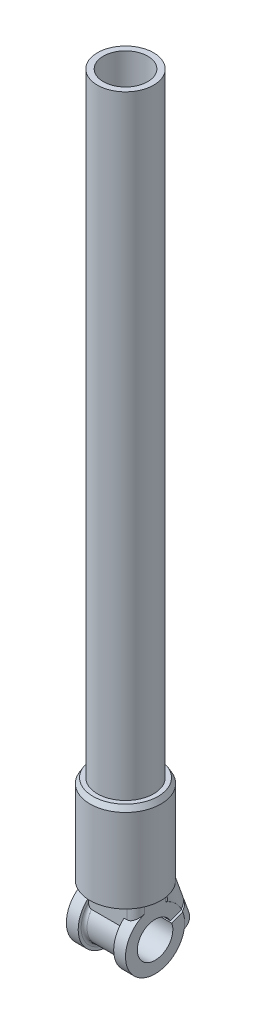
SolidWorks part; units mm, degrees
material "6061 Alloy"
ref_plane "Front Plane" through (0, 0, 0) normal (0, 0, 1) x (1, 0, 0)
ref_plane "Top Plane" through (0, 0, 0) normal (0, 1, 0) x (1, 0, 0)
ref_plane "Right Plane" through (0, 0, 0) normal (1, 0, 0) x (0, 0, -1)
sketch "Sketch1" plane through (0, 0, 0) normal (0, 0, 1) x (1, 0, 0)
  line L0 (20, -12) -> (-20, -12)
  line L1 (-20, -12) -> (-20, -20)
  line L2 (-20, -20) -> (-12, -20)
  line L3 (-12, -20) -> (-12, -18)
  line L4 (-10, -16) -> (10, -16)
  line L5 (12, -18) -> (12, -20)
  line L6 (12, -20) -> (20, -20)
  line L7 (20, -20) -> (20, -12)
  line L8 (-0.7979, 0) -> (-13.3837, 0) construction
  arc A0 (10, -16) -> (12, -18) centre (10, -18) cw
  arc A1 (-12, -18) -> (-10, -16) centre (-10, -18) cw
  point P8 (0, -16)
  point P10 (0, -12)
  point P13 (12, -16)
  point P16 (-12, -16)
  dimension "D6" = 2
  dimension "D1" = 40
  dimension "D2" = 12
  dimension "D3" = 8
  dimension "D4" = 4
  dimension "D5" = 24
revolve "Revolve1" add sketch "Sketch1" angle 360 about L8
sketch "Sketch3" plane through (0, 0, 0) normal (0, 1, 0) x (1, 0, 0)
  line L1 (-14, -13) -> (14, -13)
  line L2 (-20, -7) -> (-20, 7)
  line L3 (-14, 13) -> (14, 13)
  line L4 (20, -7) -> (20, 7)
  line L5 (-20, -13) -> (20, 13) construction
  line L6 (-20, 13) -> (20, -13) construction
  arc A0 (14, -13) -> (20, -7) centre (14, -7) ccw
  arc A1 (14, 13) -> (20, 7) centre (14, 7) cw
  arc A2 (-14, -13) -> (-20, -7) centre (-14, -7) cw
  arc A3 (-20, 7) -> (-14, 13) centre (-14, 7) cw
  point P0 (0, 0)
  dimension "D3" = 6
  dimension "D1" = 40
  dimension "D2" = 26
extrude "Boss-Extrude3" add sketch "Sketch3" against normal up to surface (15.6726 mm away) from offset 25
sketch "Sketch7" plane through (0, 0, 0) normal (0, 0, 1) x (1, 0, 0)
  line L0 (0, 25) -> (-19, 25)
  line L1 (-14, 25) -> (14, 25) construction
  line L2 (-14, 25) -> (-20, 25) construction
  line L3 (-19, 25) -> (-19, 85)
  line L4 (-19, 85) -> (-22, 85)
  line L5 (-24, 81.5359) -> (-24, 25)
  line L6 (0, 17) -> (-10, 17)
  line L7 (0, 17) -> (0, 25)
  line L9 (-24, 81.5359) -> (-22, 85)
  line L10 (-10, 17) -> (-24, 25)
  dimension "D1" = 19
  dimension "D2" = 5
  dimension "D3" = 8
  dimension "D4" = 30
  dimension "D5" = 3
  dimension "D6" = 60
  dimension "D7" = 10
revolve "Revolve2" add sketch "Sketch7" angle 360 about L7
ref_plane "Plane1" through (0, -18.7939, -6.8404) normal (0, -0.9397, -0.342) x (1, 0, 0)
sketch "Sketch11" plane through (0, -18.7939, -6.8404) normal (0, -0.9397, -0.342) x (1, 0, 0)
  line L1 (20, -14.5791) -> (20, -1.4234) construction
  line L3 (-20, 20) -> (-20, -20) construction
  arc A0 (0, -23.1984) -> (0, -10.5493) centre (9, -16.8738) ccw
  arc A1 (0, -10.5493) -> (0, -23.1984) centre (-9, -16.8738) ccw
  ellipse E0 centre (0, -8.5505) end of major axis (24, -8.5505) minor radius 22.5526 construction
  dimension "D2" = 22
extrude "Boss-Extrude6" add sketch "Sketch11" against normal up to surface (23.9263 mm away) from offset 10 offset against normal yes
sketch "Sketch12" plane through (0, -9.3969, -3.4202) normal (0, -0.9397, -0.342) x (1, 0, 0)
  circle A0 centre (-9, -21.1984) radius 3
  circle A1 centre (9, -21.1984) radius 3
  dimension "D1" = 6
  dimension "D2" = 18
  dimension "D3" = 9
  dimension "D4" = 2
extrude "Cut-Extrude4" cut sketch "Sketch12" against normal blind 20
sketch "Sketch13" plane through (-20, 0, 0) normal (-1, 0, 0) x (0, 0, 1)
  line L1 (-11.2763, 4.1042) -> (-26.3114, 9.5766)
  line L2 (-10.4346, 5.9262) -> (-25.6274, 11.4559)
  line L3 (-26.3114, 9.5766) -> (-25.6274, 11.4559)
  line L11 (-20.8347, 24.2546) -> (-29.613, 0.1365) construction
  arc A0 (-11.2763, 4.1042) -> (-10.4346, 5.9262) centre (0, 0) ccw
  circle A1 centre (0, 0) radius 12 construction
  dimension "D1" = 2
  dimension "D2" = 16
extrude "Cut-Extrude5" cut sketch "Sketch13" against normal through all
sketch "Sketch14" plane through (0, 0, 0) normal (1, 0, 0) x (0, 0, -1)
  line L0 (-19, 25) -> (-19, 500)
  line L1 (-19, 500) -> (-15, 500)
  line L2 (-15, 500) -> (-15, 25)
  line L3 (19, 25) -> (-19, 25) construction
  line L4 (-15, 25) -> (-19, 25)
  line L5 (0, 0) -> (0, 62.313) construction
  dimension "D1" = 4
  dimension "D2" = 475
revolve "Revolve3" add sketch "Sketch14" angle 360 about L5
